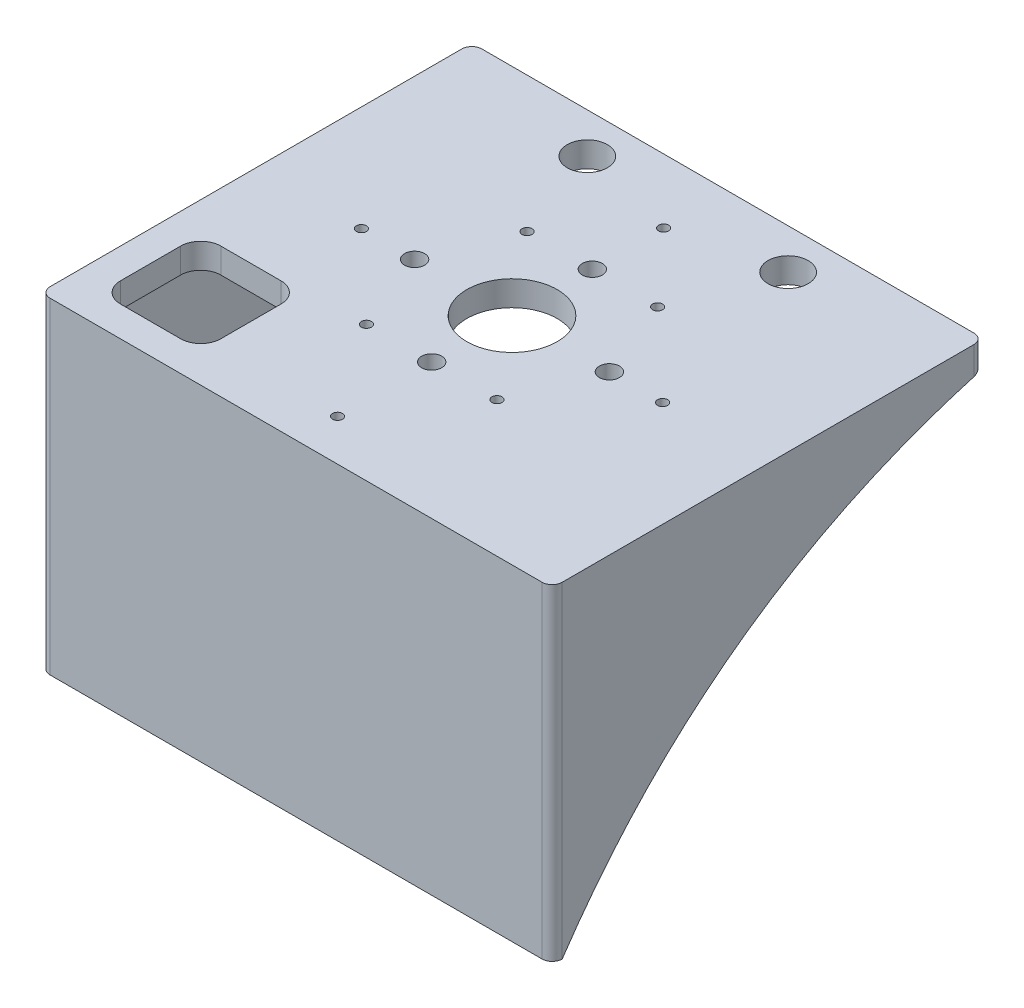
SolidWorks part; units mm, degrees
ref_plane "Front Plane" through (0, 0, 0) normal (0, 0, 1) x (1, 0, 0)
ref_plane "Top Plane" through (0, 0, 0) normal (0, 1, 0) x (1, 0, 0)
ref_plane "Right Plane" through (0, 0, 0) normal (1, 0, 0) x (0, 0, -1)
sketch "Sketch1" plane through (0, 0, 0) normal (0, 1, 0) x (1, 0, 0)
  line L0 (-9.7, 0) -> (9.7, 0)
  line L1 (-25.5, -21.5) -> (25.5, -21.5)
  line L2 (-25.5, -21.5) -> (-25.5, 21.5)
  line L3 (-25.5, 21.5) -> (25.5, 21.5)
  line L4 (25.5, -21.5) -> (25.5, 21.5)
  line L6 (-25.5, 21.5) -> (25.5, -21.5) construction
  line L7 (-28.05, 0) -> (28.05, 0) construction
  line L8 (0, -8) -> (0, 8)
  line L9 (0, -23.65) -> (0, 23.65) construction
  line L10 (-10, 21.5) -> (-10, 17.5)
  line L11 (-10, 17.5) -> (0, 17.5)
  line L13 (-20.5, -18.5) -> (-14.5, -18.5)
  line L14 (-22.5, -16.5) -> (-22.5, -10.5)
  line L15 (-20.5, -8.5) -> (-14.5, -8.5)
  line L16 (-12.5, -16.5) -> (-12.5, -10.5)
  circle A0 centre (0, 0) radius 4.5
  circle A1 centre (9.7, 0) radius 1
  circle A2 centre (-9.7, 0) radius 1
  circle A3 centre (0, 8) radius 1
  circle A4 centre (0, -8) radius 1
  circle A5 centre (-10, 17.5) radius 2
  circle A6 centre (10, 17.5) radius 2
  arc A7 (-12.5, -16.5) -> (-14.5, -18.5) centre (-14.5, -16.5) cw
  arc A8 (-20.5, -18.5) -> (-22.5, -16.5) centre (-20.5, -16.5) cw
  arc A9 (-20.5, -8.5) -> (-22.5, -10.5) centre (-20.5, -10.5) ccw
  arc A10 (-14.5, -8.5) -> (-12.5, -10.5) centre (-14.5, -10.5) cw
  circle A11 centre (-15, 0) radius 0.5
  circle A12 centre (15, 0) radius 0.5
  circle A13 centre (0, -17.3753) radius 0.5
  circle A14 centre (0, 15.1037) radius 0.5
  circle A15 centre (6.5, 8) radius 0.5
  circle A16 centre (-6.5, 8) radius 0.5
  circle A17 centre (-6.5, -8) radius 0.5
  circle A18 centre (6.5, -8) radius 0.5
  point P0 (0, 0)
  point P13 (0, 0)
  point P19 (0, 0)
  point P28 (-19.3945, -16.3522)
  point P37 (-22.5, -18.5)
  point P40 (-22.5, -8.5)
  point P43 (-12.5, -8.5)
  dimension "D3" = 19.4
  dimension "D5" = 10
  dimension "D7" = 10
  dimension "D11" = 2
  dimension "D12" = 30
  dimension "D1" = 51
  dimension "D2" = 43
  dimension "D4" = 16
  dimension "D6" = 4
  dimension "D8" = 3
  dimension "D9" = 10
  dimension "D10" = 3
  dimension "D13" = 15
  dimension "D14" = 13
  dimension "D15" = 6.5
  dimension "D16" = 8
  dimension "D17" = 16
  dimension "D18" = 16
  dimension "D19" = 13
  dimension "D20" = 6.5
extrude "Boss-Extrude1" add sketch "Sketch1" along normal blind 2.5
fillet "Fillet1" radius 1 4 edges at (25.5, 1.25, 21.5) (25.5, 1.25, -21.5) (-25.5, 1.25, -21.5) (-25.5, 1.25, 21.5)
sketch "Sketch2" plane through (0, 0, 0) normal (0, -1, 0) x (1, 0, 0)
  line L0 (-23.5, -21.5) -> (-23.5, 18.5)
  line L1 (-24.5, -21.5) -> (24.5, -21.5) construction
  line L2 (-22.5, 19.5) -> (22.5, 19.5)
  line L3 (23.5, 18.5) -> (23.5, -21.5)
  line L4 (-25.5, 20.5) -> (-25.5, -20.5) construction
  line L5 (-24.5, 21.5) -> (24.5, 21.5) construction
  line L6 (25.5, 20.5) -> (25.5, -20.5) construction
  line L10 (-24.5, -21.5) -> (-23.5, -21.5)
  line L11 (24.5, -21.5) -> (23.5, -21.5)
  line L13 (25.5, -20.5) -> (25.5, 20.5)
  line L14 (24.5, 21.5) -> (-24.5, 21.5)
  line L15 (-25.5, 20.5) -> (-25.5, -20.5)
  line L16 (25.5, -20.5) -> (25.5, 20.5)
  line L17 (24.5, 21.5) -> (-24.5, 21.5)
  line L18 (-25.5, 20.5) -> (-25.5, -20.5)
  arc A0 (23.5, 18.5) -> (22.5, 19.5) centre (22.5, 18.5) ccw
  arc A1 (-22.5, 19.5) -> (-23.5, 18.5) centre (-22.5, 18.5) ccw
  arc A10 (-25.5, -20.5) -> (-24.5, -21.5) centre (-24.5, -20.5) ccw
  arc A11 (24.5, -21.5) -> (25.5, -20.5) centre (24.5, -20.5) ccw
  arc A12 (25.5, 20.5) -> (24.5, 21.5) centre (24.5, 20.5) ccw
  arc A13 (-24.5, 21.5) -> (-25.5, 20.5) centre (-24.5, 20.5) ccw
  arc A14 (-25.5, -20.5) -> (-24.5, -21.5) centre (-24.5, -20.5) ccw
  arc A15 (24.5, -21.5) -> (25.5, -20.5) centre (24.5, -20.5) ccw
  arc A16 (25.5, 20.5) -> (24.5, 21.5) centre (24.5, 20.5) ccw
  arc A17 (-24.5, 21.5) -> (-25.5, 20.5) centre (-24.5, 20.5) ccw
  dimension "D4" = 1
  dimension "D1" = 2
  dimension "D2" = 2
  dimension "D3" = 2
  dimension "D5" = 0
extrude "Boss-Extrude2" add sketch "Sketch2" along normal blind 30
sketch "Sketch3" plane through (25.5, 0, 0) normal (1, 0, 0) x (0, 0, -1)
  line L0 (23.65, 0) -> (-23.65, 0) construction
  line L1 (21.5, 2.5) -> (21.5, -30) construction
  line L2 (-20.5, -30) -> (-30.6155, -33.1036)
  line L3 (-30.6155, -33.1036) -> (-29.1662, 8.6229)
  line L4 (-29.1662, 8.6229) -> (21.0746, 8.6229)
  line L5 (21.0746, 8.6229) -> (27.4151, 8.1398)
  line L6 (27.4151, 8.1398) -> (21.5, 0)
  line L7 (-20.5, -30) -> (-11.7148, -35.8813)
  line L8 (-11.7148, -35.8813) -> (34.7821, -34.6132)
  line L9 (34.7821, -34.6132) -> (27.4151, -3.2127)
  line L10 (27.4151, -3.2127) -> (21.5, 0)
  spline S0 degree 2 poles (-20.5, -30) (-5.214, -7.3279) (21.5, 0) knots 0 0 0 1 1 1
  line M8 (-20.5, -30) -> (20.5, -30)
  line M9 (20.5, -30) -> (20.5, 2.5)
extrude "Cut-Extrude1" cut sketch "Sketch3" against normal blind 67 contours S0 M8 M9 | S0 L7 L8 L9 L10 M9 M8
